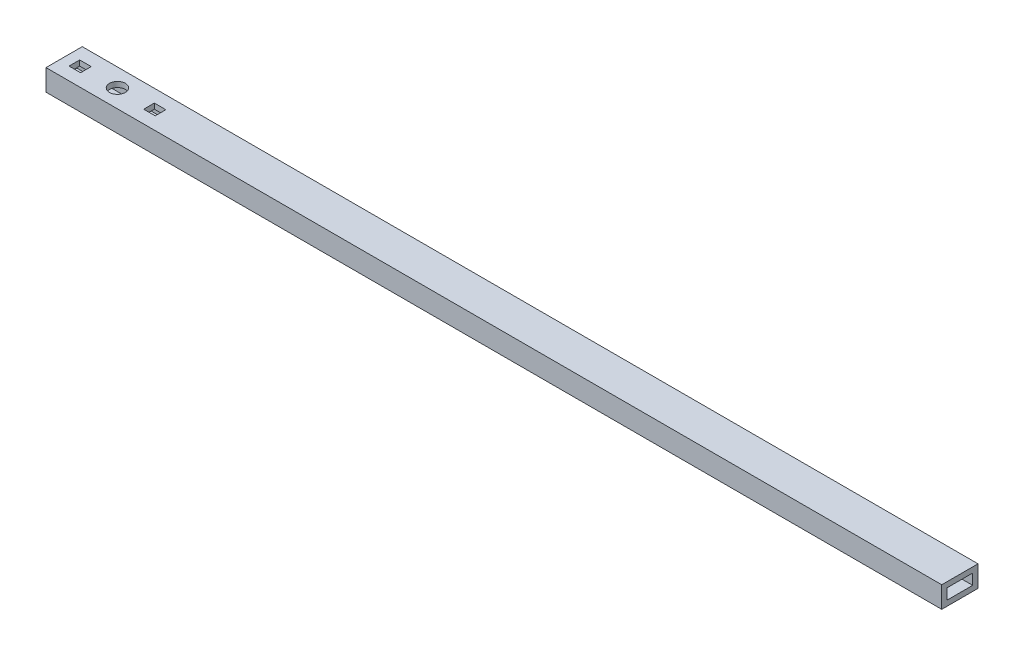
SolidWorks part; units mm, degrees
material "Acrylique (impact moyen-haut)"
ref_plane "Plan de face" through (0, 0, 0) normal (0, 0, 1) x (1, 0, 0)
ref_plane "Plan de dessus" through (0, 0, 0) normal (0, 1, 0) x (1, 0, 0)
ref_plane "Plan de droite" through (0, 0, 0) normal (1, 0, 0) x (0, 0, -1)
sketch "Esquisse1" plane through (0, 0, 0) normal (1, 0, 0) x (0, 0, -1)
  line L0 (-7.62, -3.175) -> (-7.62, 3.175)
  line L1 (-10.795, -6.35) -> (10.795, -6.35)
  line L2 (-10.795, -6.35) -> (-10.795, 6.35)
  line L3 (-10.795, 6.35) -> (10.795, 6.35)
  line L4 (10.795, -6.35) -> (10.795, 6.35)
  line L5 (-10.795, -6.35) -> (10.795, 6.35) construction
  line L6 (-10.795, 6.35) -> (10.795, -6.35) construction
  line L7 (-7.62, 3.175) -> (7.62, 3.175)
  line L8 (7.62, -3.175) -> (7.62, 3.175)
  line L9 (-7.62, -3.175) -> (7.62, -3.175)
  point P0 (0, 0)
  dimension "D1" = 12.7
  dimension "D2" = 21.59
  dimension "D3" = 3.175
extrude "Boss.-Extru.1" add sketch "Esquisse1" along normal blind 596.9
sketch "Esquisse2" plane through (0, -6.35, 0) normal (0, -1, 0) x (1, 0, 0)
  line L0 (596.9, 10.795) -> (0, 10.795) construction
  line L1 (6.096, -3.175) -> (12.954, -3.175)
  line L2 (6.096, -3.175) -> (6.096, 3.175)
  line L3 (6.096, 3.175) -> (12.954, 3.175)
  line L4 (12.954, -3.175) -> (12.954, 3.175)
  line L5 (6.096, -3.175) -> (12.954, 3.175) construction
  line L6 (6.096, 3.175) -> (12.954, -3.175) construction
  line L7 (50.546, -3.175) -> (57.404, -3.175)
  line L8 (50.546, -3.175) -> (50.546, 3.175)
  line L9 (50.546, 3.175) -> (57.404, 3.175)
  line L10 (57.404, -3.175) -> (57.404, 3.175)
  line L11 (50.546, -3.175) -> (57.404, 3.175) construction
  line L12 (50.546, 3.175) -> (57.404, -3.175) construction
  circle A0 centre (31.75, 0) radius 4.7244
  point P2 (9.525, 0)
  point P7 (53.975, 0)
  point P12 (27.0016, 0)
  point P13 (14.5167, 0)
  point P15 (6.096, 0)
  point P16 (50.546, 0)
  point P19 (298.45, 10.795)
  dimension "D1" = 9.4488
  dimension "D2" = 22.225
  dimension "D3" = 22.225
  dimension "D4" = 6.35
  dimension "D5" = 6.858
  dimension "D6" = 266.7
extrude "Enlèv. mat.-Extru.1" cut sketch "Esquisse2" against normal through all
ref_plane "Plan1" through (298.45, 0, 0) normal (-1, 0, 0) x (0, 0, 1)
mirror "Symétrie1" about plane through (298.45, 0, 0) normal (-1, 0, 0) of "Enlèv. mat.-Extru.1"
sketch "Esquisse3" plane through (0, -6.35, 0) normal (0, -1, 0) x (1, 0, 0)
  line L1 (596.9, -10.795) -> (533.4, -10.795)
  line L2 (596.9, -10.795) -> (596.9, 10.795)
  line L3 (596.9, 10.795) -> (533.4, 10.795)
  line L4 (533.4, -10.795) -> (533.4, 10.795)
  line L5 (596.9, 10.795) -> (0, 10.795) construction
  dimension "D1" = 21.59
  dimension "D2" = 63.5
extrude "Enlèv. mat.-Extru.2" cut sketch "Esquisse3" against normal through all
